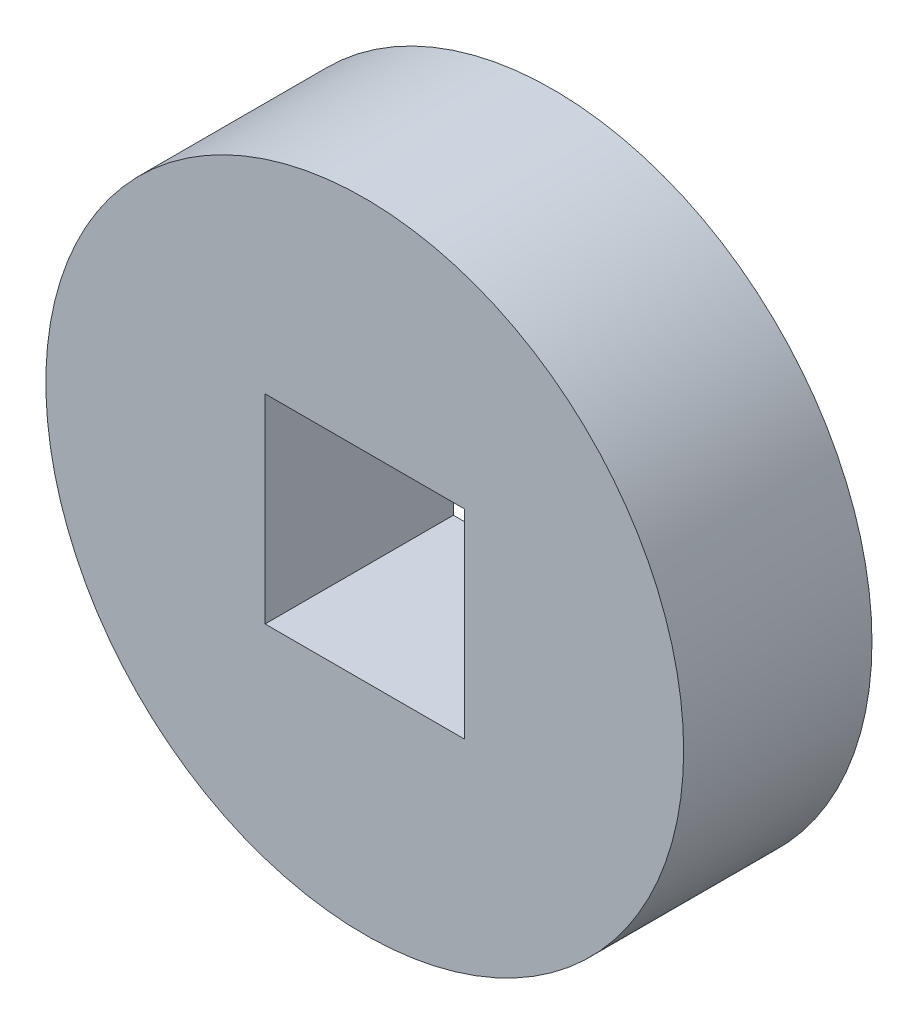
SolidWorks part; units mm, degrees
material "Custom Plastic"
ref_plane "Front Plane" through (0, 0, 0) normal (0, 0, 1) x (1, 0, 0)
ref_plane "Top Plane" through (0, 0, 0) normal (0, 1, 0) x (1, 0, 0)
ref_plane "Right Plane" through (0, 0, 0) normal (1, 0, 0) x (0, 0, -1)
sketch "Sketch1" plane through (0, 0, 0) normal (0, 0, 1) x (1, 0, 0)
  line L1 (-1.5875, 1.5875) -> (1.5875, 1.5875)
  line L2 (-1.5875, 1.5875) -> (-1.5875, -1.5875)
  line L3 (-1.5875, -1.5875) -> (1.5875, -1.5875)
  line L4 (1.5875, 1.5875) -> (1.5875, -1.5875)
  line L5 (-1.5875, 1.5875) -> (1.5875, -1.5875) construction
  line L6 (-1.5875, -1.5875) -> (1.5875, 1.5875) construction
  circle A0 centre (0, 0) radius 5.08
  point P0 (0, 0)
  dimension "D2" = 10.16
  dimension "D1" = 3.175
extrude "Boss-Extrude1" add sketch "Sketch1" along normal blind 3
